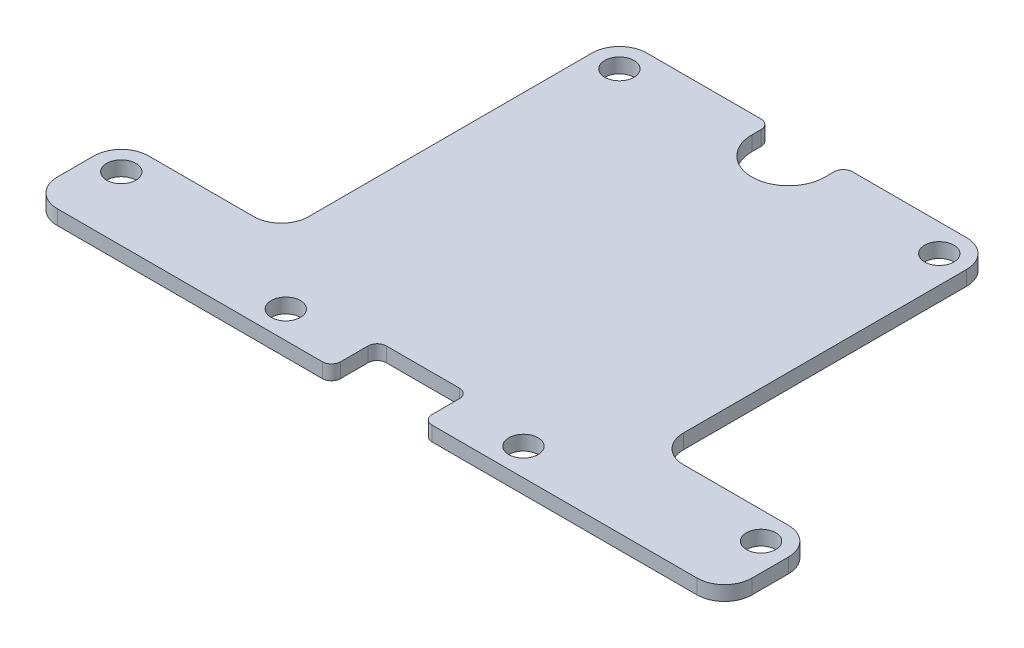
SolidWorks part; units mm, degrees
ref_plane "Front Plane" through (0, 0, 0) normal (0, 0, 1) x (1, 0, 0)
ref_plane "Top Plane" through (0, 0, 0) normal (0, 1, 0) x (1, 0, 0)
ref_plane "Right Plane" through (0, 0, 0) normal (1, 0, 0) x (0, 0, -1)
sketch "草图1" plane through (0, 0, 0) normal (0, 1, 0) x (1, 0, 0)
  line L0 (7.8417, 0) -> (77.8417, 0)
  line L2 (60.3417, 47) -> (25.3417, 47)
  line L3 (4.8417, 3) -> (4.8417, 7)
  line L4 (7.8417, 10) -> (19.3417, 10)
  line L5 (22.3417, 13) -> (22.3417, 44)
  line L6 (63.3417, 13) -> (63.3417, 44)
  line L7 (77.8417, 10) -> (66.3417, 10)
  line L8 (80.8417, 3) -> (80.8417, 7)
  arc A8 (7.8417, 0) -> (4.8417, 3) centre (7.8417, 3) cw
  arc A9 (4.8417, 7) -> (7.8417, 10) centre (7.8417, 7) cw
  arc A10 (22.3417, 13) -> (19.3417, 10) centre (19.3417, 13) cw
  arc A11 (77.8417, 0) -> (80.8417, 3) centre (77.8417, 3) ccw
  arc A12 (80.8417, 7) -> (77.8417, 10) centre (77.8417, 7) ccw
  arc A13 (66.3417, 10) -> (63.3417, 13) centre (66.3417, 13) cw
  arc A14 (63.3417, 44) -> (60.3417, 47) centre (60.3417, 44) ccw
  arc A15 (22.3417, 44) -> (25.3417, 47) centre (25.3417, 44) cw
  dimension "D1" = 3
extrude "凸台-拉伸1" add sketch "草图1" along normal blind 1.6
sketch "草图2" plane through (0, 1.6, 0) normal (0, 1, 0) x (1, 0, 0)
  line L7 (7.8417, 0) -> (77.8417, 0) construction
  line L14 (37.8417, 1) -> (37.8417, 4)
  line L15 (38.8417, 5) -> (46.8417, 5)
  line L16 (47.8417, 4) -> (47.8417, 1)
  line L18 (36.8417, 0) -> (48.8417, 0)
  arc A6 (47.8417, 1) -> (48.8417, 0) centre (48.8417, 1) ccw
  arc A7 (36.8417, 0) -> (37.8417, 1) centre (36.8417, 1) ccw
  arc A8 (46.8417, 5) -> (47.8417, 4) centre (46.8417, 4) cw
  arc A9 (37.8417, 4) -> (38.8417, 5) centre (38.8417, 4) cw
  point P10 (47.8417, 0)
  point P13 (37.8417, 0)
  dimension "D1" = 1
extrude "切除-拉伸1" cut sketch "草图2" against normal blind 10
sketch "草图3" plane through (0, 1.6, 0) normal (0, 1, 0) x (1, 0, 0)
  circle A0 centre (7.8417, 7) radius 1.6
  circle A1 centre (29.8417, 3) radius 1.6
  circle A2 centre (25.3417, 44) radius 1.6
  circle A3 centre (60.3417, 44) radius 1.6
  circle A4 centre (55.8417, 3) radius 1.6
  circle A5 centre (77.8417, 7) radius 1.6
extrude "切除-拉伸2" cut sketch "草图3" against normal through all
sketch "草图4" plane through (0, 1.6, 0) normal (0, 1, 0) x (1, 0, 0)
  line L7 (60.3417, 47) -> (25.3417, 47) construction
  line L8 (46.8417, 45) -> (46.8417, 46)
  line L9 (37.8417, 47) -> (47.8417, 47)
  line L10 (38.8417, 45) -> (38.8417, 46)
  arc A4 (38.8417, 45) -> (46.8417, 45) centre (42.8417, 45) ccw
  arc A5 (46.8417, 46) -> (47.8417, 47) centre (47.8417, 46) cw
  arc A6 (38.8417, 46) -> (37.8417, 47) centre (37.8417, 46) ccw
  point P11 (46.8417, 47)
  point P14 (38.8417, 47)
  dimension "D1" = 1
extrude "切除-拉伸3" cut sketch "草图4" against normal blind 5
